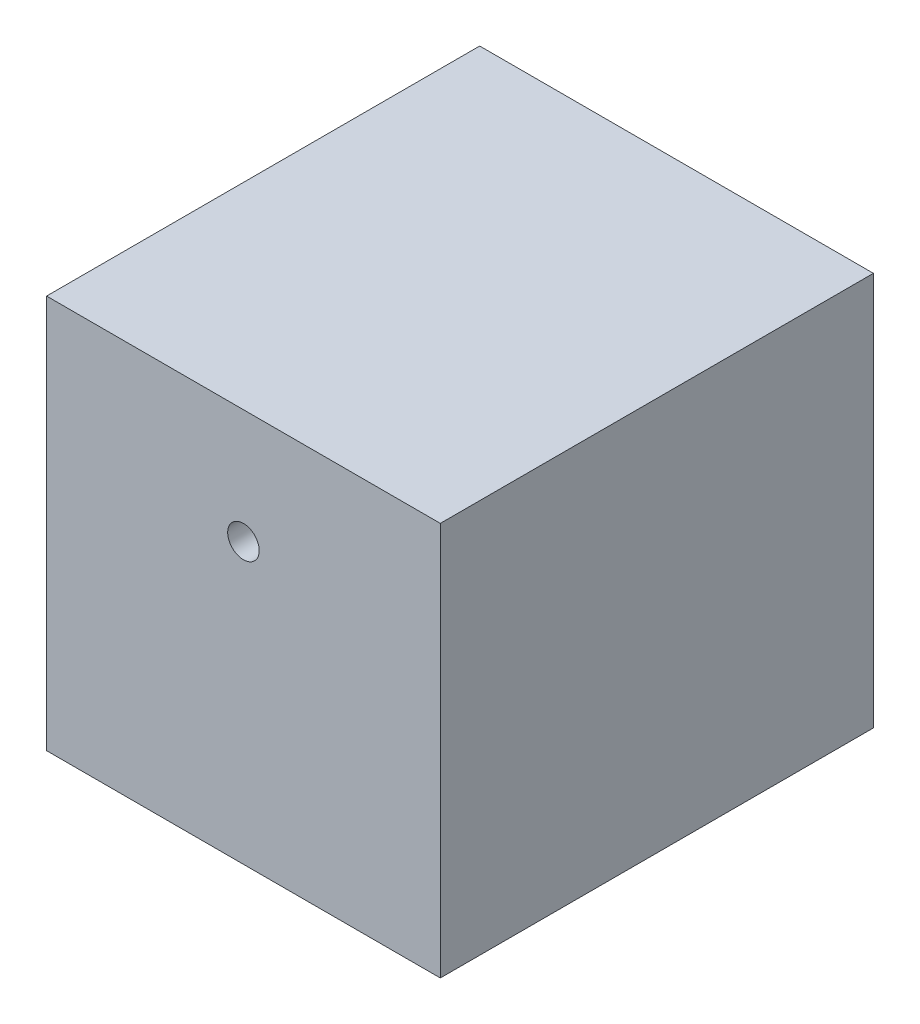
SolidWorks part; units mm, degrees
ref_plane "Front Plane" through (0, 0, 0) normal (0, 0, 1) x (1, 0, 0)
ref_plane "Top Plane" through (0, 0, 0) normal (0, 1, 0) x (1, 0, 0)
ref_plane "Right Plane" through (0, 0, 0) normal (1, 0, 0) x (0, 0, -1)
sketch "Sketch1" plane through (0, 0, 0) normal (0, 0, 1) x (1, 0, 0)
  line L1 (0, 0) -> (10, 0)
  line L2 (0, 0) -> (0, 10)
  line L3 (0, 10) -> (10, 10)
  line L4 (10, 0) -> (10, 10)
  dimension "D1" = 10
extrude "Boss-Extrude1" add sketch "Sketch1" along normal blind 11
sketch "Sketch2" plane through (0, 0, 11) normal (0, 0, 1) x (1, 0, 0)
  line L0 (0, 0) -> (10, 0) construction
  line L1 (0, 10) -> (0, 0) construction
  circle A0 centre (5, 7.1) radius 0.4
  dimension "D1" = 0.8
  dimension "D2" = 7.1
  dimension "D3" = 5
extrude "Cut-Extrude1" cut sketch "Sketch2" against normal blind 7
